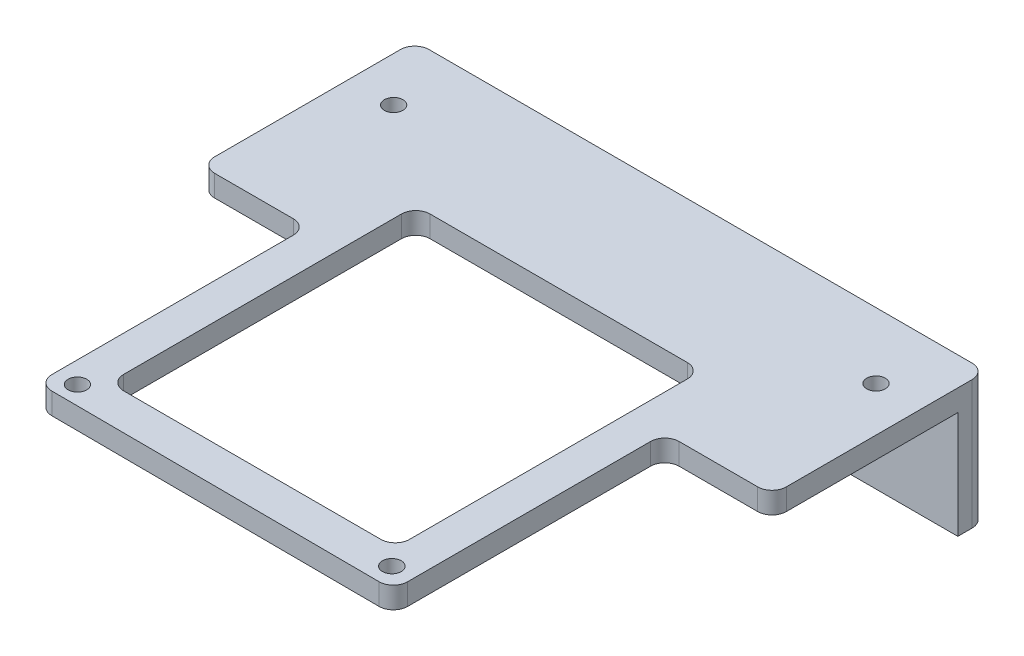
SolidWorks part; units mm, degrees
ref_plane "Front Plane" through (0, 0, 0) normal (0, 0, 1) x (1, 0, 0)
ref_plane "Top Plane" through (0, 0, 0) normal (0, 1, 0) x (1, 0, 0)
ref_plane "Right Plane" through (0, 0, 0) normal (1, 0, 0) x (0, 0, -1)
sketch "Sketch2" plane through (0, 0, 0) normal (0, -1, 0) x (1, 0, 0)
  line L1 (-23.0093, 31.2763) -> (22.9907, 31.4906)
  line L8 (22, 31.5) -> (35, 31.5) construction
  line L10 (35, -31.5) -> (-35, -31.5) construction
  line L12 (25, -4.5) -> (25, 29.4907)
  line L15 (-27, -6.5) -> (-38, -6.5)
  line L17 (38, -36.5) -> (-38, -36.5)
  line L18 (40, -34.5) -> (40, -8.5)
  line L19 (38, -6.5) -> (27, -6.5)
  line L20 (-40, -34.5) -> (-40, -8.5)
  line L23 (-25, -4.5) -> (-25, 29.2763)
  circle A4 centre (22.0091, 28.7123) radius 1.3153
  circle A5 centre (-22, 28.7) radius 1.3
  circle A6 centre (-33.75, -27.3) radius 1.3
  circle A7 centre (33.75, -27.3) radius 1.3
  arc A8 (38, -36.5) -> (40, -34.5) centre (38, -34.5) ccw
  arc A9 (40, -8.5) -> (38, -6.5) centre (38, -8.5) ccw
  arc A10 (-38, -36.5) -> (-40, -34.5) centre (-38, -34.5) cw
  arc A11 (-38, -6.5) -> (-40, -8.5) centre (-38, -8.5) ccw
  arc A12 (-25, -4.5) -> (-27, -6.5) centre (-27, -4.5) cw
  arc A13 (25, -4.5) -> (27, -6.5) centre (27, -4.5) ccw
  arc A14 (22.9907, 31.4906) -> (25, 29.4907) centre (23, 29.4907) cw
  arc A15 (-23.0093, 31.2763) -> (-25, 29.2763) centre (-23, 29.2763) ccw
  point P8 (0, 0)
  point P16 (0, -31.5)
  point P26 (40, -36.5)
  point P33 (-40, -36.5)
  point P36 (-40, -6.5)
  point P39 (-25, -6.5)
  point P44 (25, 31.5)
  point P47 (0, 0)
  point P48 (0, 0)
  point P49 (0, 0)
  dimension "D1" = 2
  dimension "D2" = 30
  dimension "D3" = 80
  dimension "D6" = 6.25
  dimension "D9" = 36.5
extrude "Boss-Extrude1" add sketch "Sketch2" along normal blind 3
sketch "Sketch3" plane through (0, -3, 0) normal (0, -1, 0) x (1, 0, 0)
  line L1 (-18, 26.2337) -> (18, 26.2337)
  line L2 (-20, 24.2337) -> (-20, -14.6434)
  line L3 (-18, -16.6434) -> (18, -16.6434)
  line L4 (20, 24.2337) -> (20, -14.6434)
  arc A2 (-20, -14.6434) -> (-18, -16.6434) centre (-18, -14.6434) ccw
  arc A3 (18, -16.6434) -> (20, -14.6434) centre (18, -14.6434) ccw
  arc A4 (18, 26.2337) -> (20, 24.2337) centre (18, 24.2337) cw
  arc A5 (-18, 26.2337) -> (-20, 24.2337) centre (-18, 24.2337) ccw
  point P4 (0, 0)
  point P5 (0, 0)
  point P23 (20, 26.2337)
  point P26 (-20, 26.2337)
  dimension "D3" = 20
  dimension "D4" = 40
extrude "Cut-Extrude1" cut sketch "Sketch3" against normal blind 10
sketch "Sketch5" plane through (0, -3, 0) normal (0, -1, 0) x (1, 0, 0)
  line L0 (-40, -8.5) -> (-40, -34.5) construction
  line L1 (-40, -32.5) -> (40, -32.5)
  line L2 (-40, -32.5) -> (-40, -34.5)
  line L3 (-38, -36.5) -> (38, -36.5)
  line L4 (40, -32.5) -> (40, -34.5)
  line L5 (40, -34.5) -> (40, -8.5) construction
  line L6 (-38, -36.5) -> (38, -36.5) construction
  arc A0 (-38, -36.5) -> (-40, -34.5) centre (-38, -34.5) cw
  arc A1 (38, -36.5) -> (40, -34.5) centre (38, -34.5) ccw
  point P14 (40, -36.5)
  dimension "D2" = 2
  dimension "D3" = 2
  dimension "D1" = 4
extrude "Boss-Extrude3" add sketch "Sketch5" along normal blind 15
sketch "Sketch6" plane through (0, 0, -32.5) normal (0, 0, 1) x (1, 0, 0)
  line L0 (40, -18) -> (-40, -18) construction
  circle A0 centre (-25, -10.5) radius 2.2
  circle A1 centre (25, -10.5) radius 2.2
  dimension "D1" = 4.4
  dimension "D2" = 4.4
  dimension "D3" = 7.5
  dimension "D4" = 7.5
  dimension "D5" = 50
  dimension "D6" = 25
extrude "Cut-Extrude2" cut sketch "Sketch6" against normal blind 10
